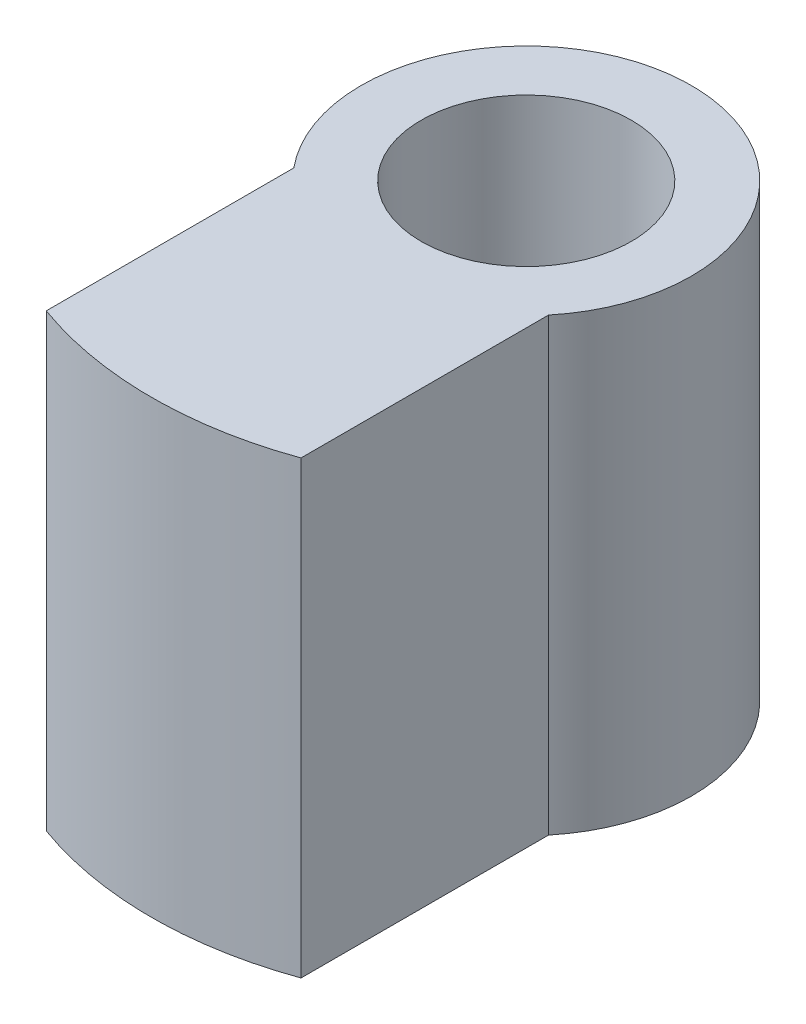
SolidWorks part; units mm, degrees
ref_plane "Front Plane" through (0, 0, 0) normal (0, 0, 1) x (1, 0, 0)
ref_plane "Top Plane" through (0, 0, 0) normal (0, 1, 0) x (1, 0, 0)
ref_plane "Right Plane" through (0, 0, 0) normal (1, 0, 0) x (0, 0, -1)
sketch "Sketch1" plane through (0, 0, 0) normal (0, 1, 0) x (1, 0, 0)
  line L3 (-4.2426, -3.5) -> (-4.2426, -11.7437)
  line L4 (4.2426, -3.5) -> (4.2426, -11.7437)
  circle A0 centre (0, 0) radius 3.5
  arc A1 (-4.2426, -11.7437) -> (4.2426, -11.7437) centre (0, 0) ccw
  arc A2 (4.2426, -3.5) -> (-4.2426, -3.5) centre (0, 0) ccw
  point P7 (0, 0)
extrude "Boss-Extrude1" add sketch "Sketch1" along normal blind 15
